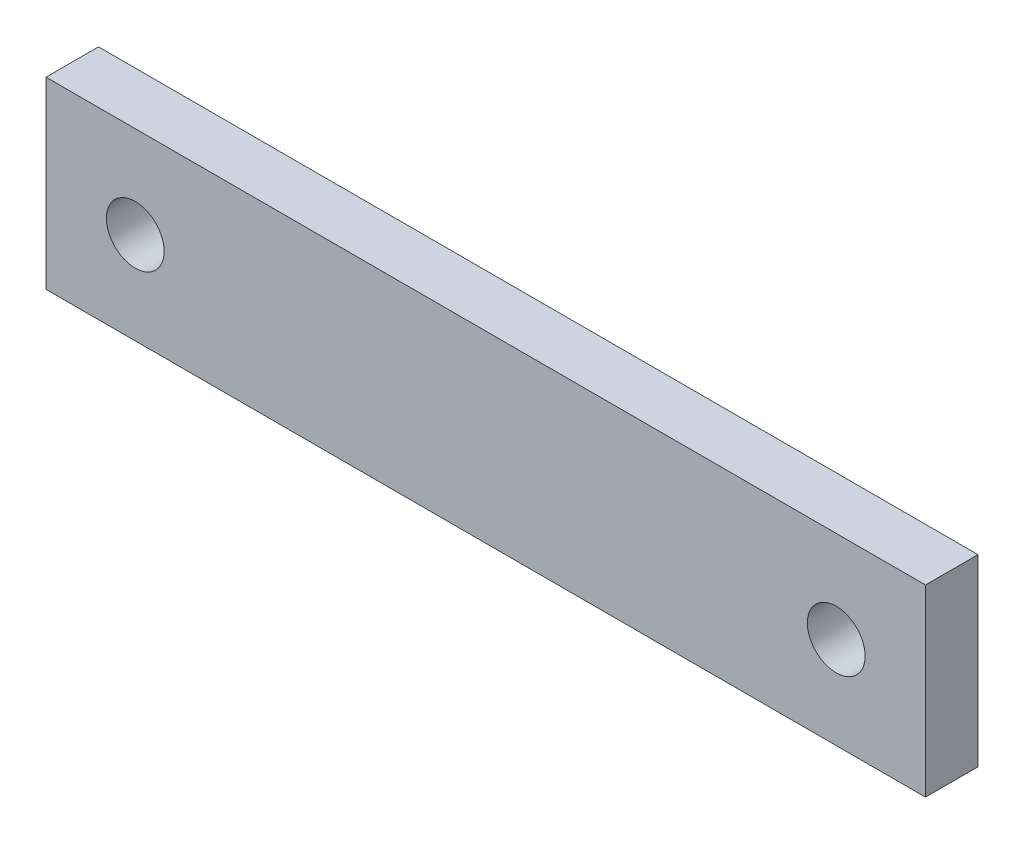
SolidWorks part; units mm, degrees
ref_plane "前视基准面" through (0, 0, 0) normal (0, 0, 1) x (1, 0, 0)
ref_plane "上视基准面" through (0, 0, 0) normal (0, 1, 0) x (1, 0, 0)
ref_plane "右视基准面" through (0, 0, 0) normal (1, 0, 0) x (0, 0, -1)
sketch "草图1" plane through (0, 0, 0) normal (0, 0, 1) x (1, 0, 0)
  line L1 (0, 0) -> (335, 0)
  line L2 (0, 0) -> (0, 70)
  line L3 (0, 70) -> (335, 70)
  line L4 (335, 0) -> (335, 70)
  dimension "D1" = 335
  dimension "D2" = 70
extrude "凸台-拉伸1" add sketch "草图1" along normal blind 20
sketch "草图2" plane through (0, 0, 20) normal (0, 0, 1) x (1, 0, 0)
  line L0 (-1000, 35) -> (49000, 35) construction
  line L1 (0, 70) -> (0, 0) construction
  line L2 (167.5, -930) -> (167.5, 49070) construction
  line L3 (335, 70) -> (0, 70) construction
  circle A0 centre (34, 35) radius 11
  circle A1 centre (301, 35) radius 11
  point P5 (0, 35)
  point P10 (167.5, 70)
  dimension "D1" = 22
  dimension "D2" = 267
extrude "切除-拉伸1" cut sketch "草图2" against normal through all
